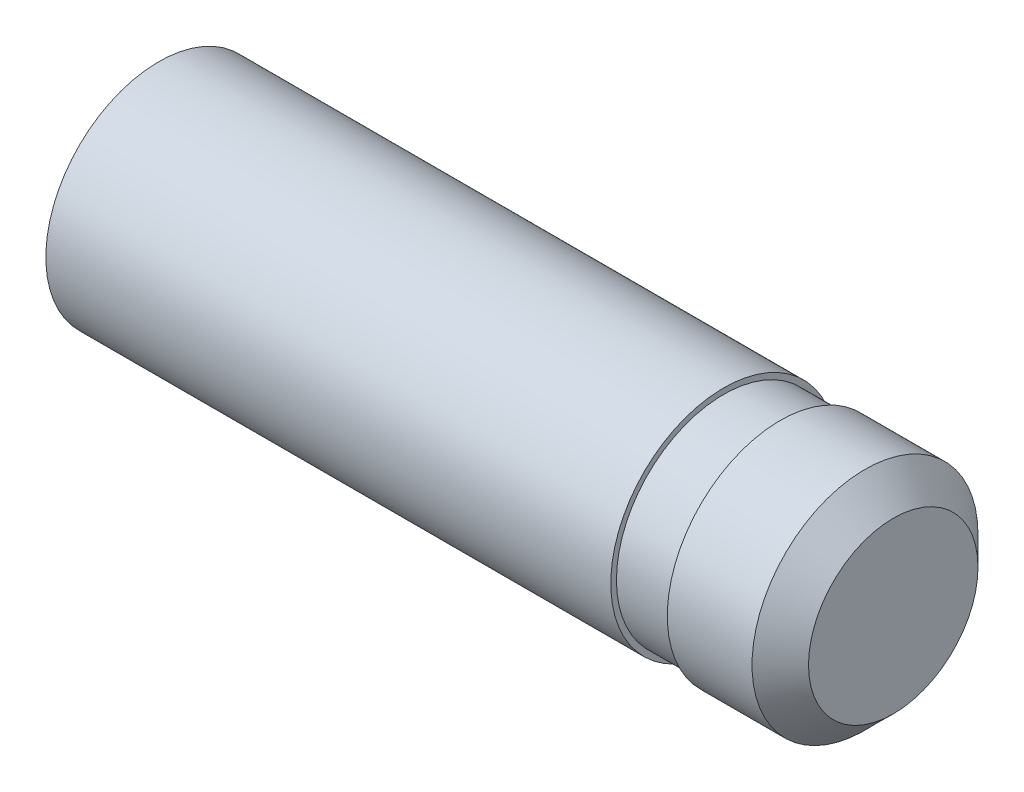
SolidWorks part; units mm, degrees
ref_plane "Front Plane" through (0, 0, 0) normal (0, 0, 1) x (1, 0, 0)
ref_plane "Top Plane" through (0, 0, 0) normal (0, 1, 0) x (1, 0, 0)
ref_plane "Right Plane" through (0, 0, 0) normal (1, 0, 0) x (0, 0, -1)
sketch "Sketch1" plane through (0, 0, 0) normal (1, 0, 0) x (0, 0, -1)
  circle A0 centre (0, 0) radius 2
  dimension "D1" = 4
extrude "Boss-Extrude1" add sketch "Sketch1" along normal blind 10
sketch "Sketch2" plane through (10, 0, 0) normal (1, 0, 0) x (0, 0, -1)
  circle A0 centre (0, 0) radius 1.9
  dimension "D1" = 3.8
extrude "Boss-Extrude2" add sketch "Sketch2" along normal blind 1
sketch "Sketch3" plane through (11, 0, 0) normal (1, 0, 0) x (0, 0, -1)
  circle A0 centre (0, 0) radius 2
extrude "Boss-Extrude3" add sketch "Sketch3" along normal blind 2
chamfer "Chamfer1" distance 0.5 angle 45 1 edges at (13, 0, -2)
